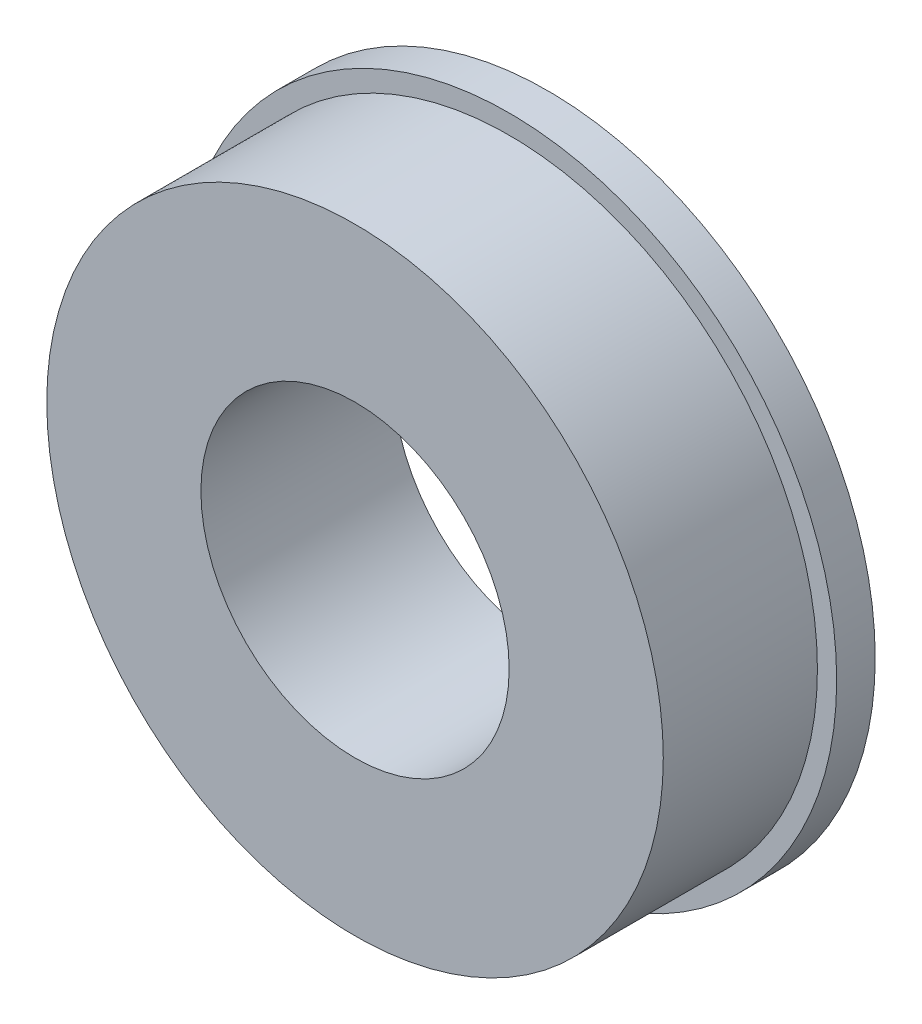
SolidWorks part; units mm, degrees
material "合金钢"
ref_plane "前视基准面" through (0, 0, 0) normal (0, 0, 1) x (1, 0, 0)
ref_plane "上视基准面" through (0, 0, 0) normal (0, 1, 0) x (1, 0, 0)
ref_plane "右视基准面" through (0, 0, 0) normal (1, 0, 0) x (0, 0, -1)
sketch "草图1" plane through (0, 0, 0) normal (0, 0, 1) x (1, 0, 0)
  circle A0 centre (0, 0) radius 8.5
  dimension "D1" = 17
extrude "凸台-拉伸1" add sketch "草图1" along normal blind 1
sketch "草图2" plane through (0, 0, 1) normal (0, 0, 1) x (1, 0, 0)
  circle A0 centre (0, 0) radius 8
  dimension "D1" = 16
extrude "凸台-拉伸2" add sketch "草图2" along normal blind 4
sketch "草图3" plane through (0, 0, 5) normal (0, 0, 1) x (1, 0, 0)
  circle A0 centre (0, 0) radius 4
  dimension "D1" = 8
extrude "切除-拉伸1" cut sketch "草图3" against normal up to surface (5 mm away) up to face at (8.5, 0, 0)
